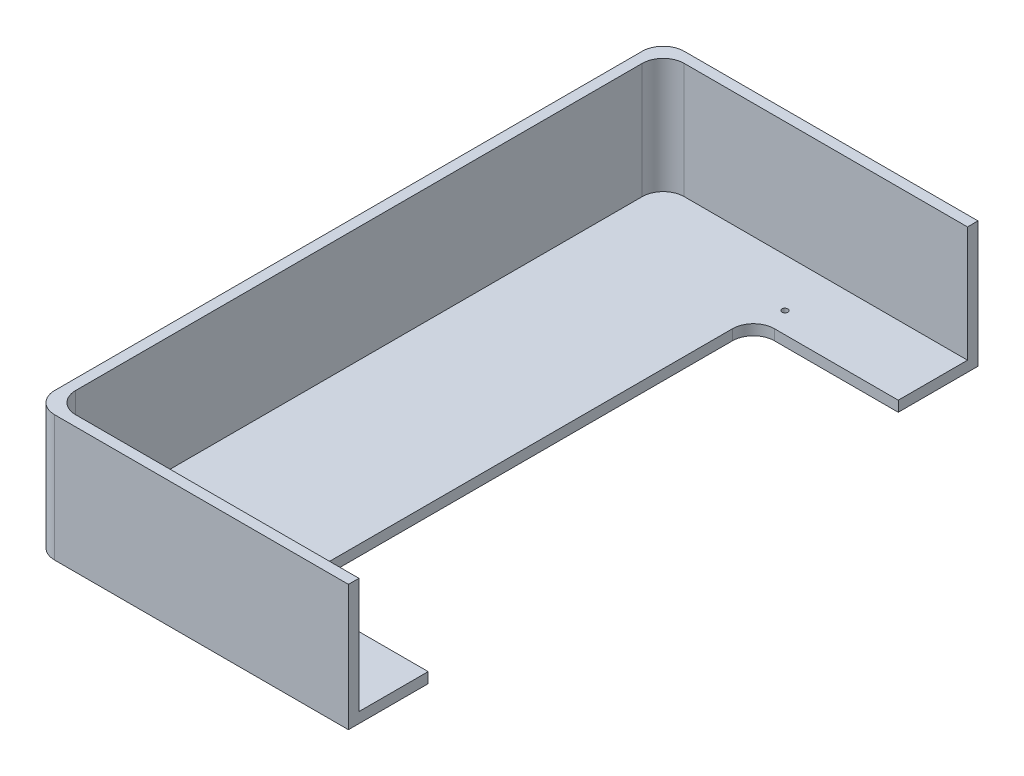
SolidWorks part; units mm, degrees
ref_plane "前视基准面" through (0, 0, 0) normal (0, 0, 1) x (1, 0, 0)
ref_plane "上视基准面" through (0, 0, 0) normal (0, 1, 0) x (1, 0, 0)
ref_plane "右视基准面" through (0, 0, 0) normal (1, 0, 0) x (0, 0, -1)
other "Configuration Table"
sketch "草图1" plane through (0, 0, 0) normal (0, 1, 0) x (1, 0, 0)
  line L1 (0, 0) -> (-150, 0)
  line L2 (0, 0) -> (0, -300)
  line L3 (0, -300) -> (-150, -300)
  line L4 (-150, 0) -> (-150, -300)
  dimension "D1" = 300
  dimension "D2" = 150
extrude "凸台-拉伸1" add sketch "草图1" along normal blind 60
sketch "草图2" plane through (0, 60, 0) normal (0, 1, 0) x (1, 0, 0)
  line L1 (-5, -5) -> (-145, -5)
  line L2 (-145, -5) -> (-145, -295)
  line L3 (-145, -295) -> (-5, -295)
  line L4 (0, -300) -> (0, 0)
  line L5 (0, 0) -> (-150, 0)
  line L6 (-150, 0) -> (-150, -300)
  line L7 (-150, -300) -> (0, -300)
  line L8 (0, -300) -> (0, 0) construction
  line L9 (0, 0) -> (-150, 0) construction
  line L10 (-150, 0) -> (-150, -300) construction
  line L11 (-150, -300) -> (0, -300) construction
  line L12 (-5, -295) -> (-5, -5) construction
  line L13 (-5, -5) -> (0, -5)
  line L14 (0, -5) -> (0, -295)
  line L15 (0, -295) -> (-5, -295)
  dimension "D1" = 0
  dimension "D2" = 5
extrude "切除-拉伸1" cut sketch "草图2" against normal offset from surface (55 mm away) 5 up to face at (-75, 0, 150)
sketch "草图3" plane through (0, 5, 0) normal (0, 1, 0) x (1, 0, 0)
  line L0 (0, -295) -> (0, -5) construction
  line L1 (0, -38) -> (-69, -38)
  line L2 (0, -38) -> (0, -262)
  line L3 (0, -262) -> (-69, -262)
  line L4 (-69, -38) -> (-69, -262)
  line L5 (-145, -150) -> (67.1801, -150) construction
  line L6 (-145, -5) -> (-145, -295) construction
  dimension "D1" = 69
  dimension "D2" = 224
extrude "切除-拉伸2" cut sketch "草图3" against normal up to surface (5 mm away) up to face at (-75, 0, 150)
sketch "草图4" plane through (0, 5, 0) normal (0, 1, 0) x (1, 0, 0)
  line L0 (-145, -150) -> (93.9069, -150) construction
  line L1 (-145, -5) -> (-145, -295) construction
  line L2 (0, -38) -> (0, -5) construction
  circle A0 centre (-64, -28) radius 1.4
  circle A1 centre (-64, -272) radius 1.4
  dimension "D2" = 2.8
  dimension "D3" = 244
  dimension "D1" = 64
extrude "切除-拉伸3" cut sketch "草图4" against normal up to surface (5 mm away) up to face at (-54.75, 0, 150)
fillet "圆角1" radius 10 6 edges at (-69, 2.5, 262) (-145, 32.5, 295) (-150, 30, 300) (-69, 2.5, 38) (-150, 30, 0) (-145, 32.5, 5)
